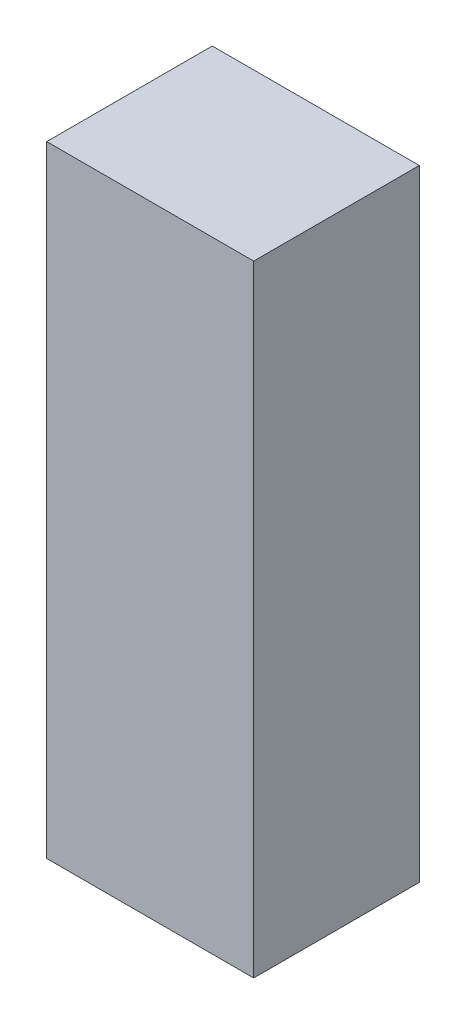
SolidWorks part; units mm, degrees
ref_plane "Front Plane" through (0, 0, 0) normal (0, 0, 1) x (1, 0, 0)
ref_plane "Top Plane" through (0, 0, 0) normal (0, 1, 0) x (1, 0, 0)
ref_plane "Right Plane" through (0, 0, 0) normal (1, 0, 0) x (0, 0, -1)
sketch "Sketch1" plane through (0, 0, 0) normal (0, 1, 0) x (1, 0, 0)
  line L1 (-5, -4) -> (5, -4)
  line L2 (-5, -4) -> (-5, 4)
  line L3 (-5, 4) -> (5, 4)
  line L4 (5, -4) -> (5, 4)
  line L5 (-5, -4) -> (5, 4) construction
  line L6 (-5, 4) -> (5, -4) construction
  point P0 (0, 0)
  dimension "D1" = 10
  dimension "D2" = 8
extrude "Boss-Extrude1" add sketch "Sketch1" along normal blind 30
